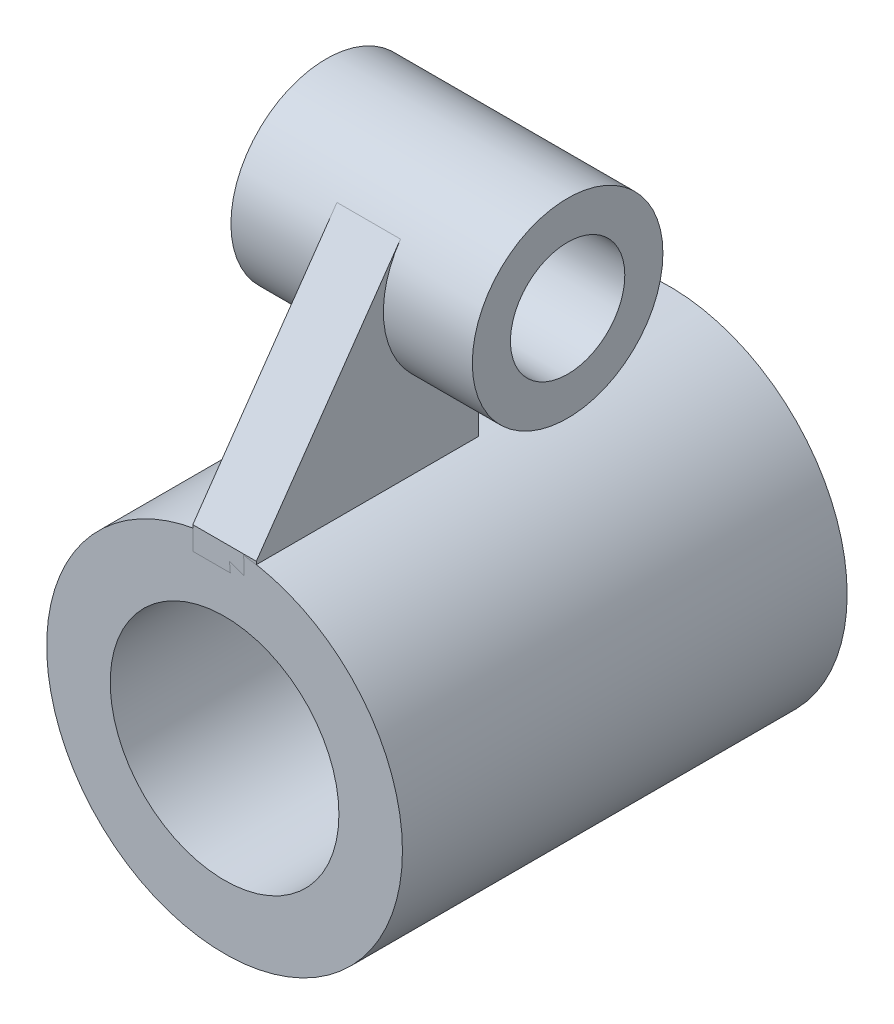
SolidWorks part; units mm, degrees
ref_plane "Front Plane" through (0, 0, 0) normal (0, 0, 1) x (1, 0, 0)
ref_plane "Top Plane" through (0, 0, 0) normal (0, 1, 0) x (1, 0, 0)
ref_plane "Right Plane" through (0, 0, 0) normal (1, 0, 0) x (0, 0, -1)
sketch "Sketch1" plane through (0, 0, 0) normal (0, 0, 1) x (1, 0, 0)
  circle A0 centre (0, 0) radius 9
  dimension "D1" = 18
extrude "Extrude-Thin1" add sketch "Sketch1" along normal mid plane 35 thin
sketch "Sketch2" plane through (0, 0, 0) normal (1, 0, 0) x (0, 0, -1)
  circle A0 centre (0, 26) radius 4.5
  point P2 (0, 0)
  dimension "D1" = 9
  dimension "D2" = 26
extrude "Extrude-Thin2" add sketch "Sketch2" along normal mid plane 19 separate body thin
sketch "Sketch3" plane through (0, 0, 0) normal (1, 0, 0) x (0, 0, -1)
  line L0 (-17.5, 14) -> (-6.154, 30.287)
  line L1 (0, 18.5) -> (0, 14)
  line L2 (17.5, 14) -> (-17.5, 14) construction
  line L4 (0, 14) -> (0, 12.1832)
  line L5 (0, 12.1832) -> (-17.5, 12.1832)
  line L6 (-17.5, 14) -> (-17.5, -14) construction
  line L7 (-17.5, 12.1832) -> (-17.5, 14)
  circle A0 centre (0, 26) radius 7.5 construction
  arc A1 (0, 18.5) -> (-6.154, 30.287) centre (0, 26) ccw
extrude "Boss-Extrude1" add sketch "Sketch3" along normal mid plane 5
